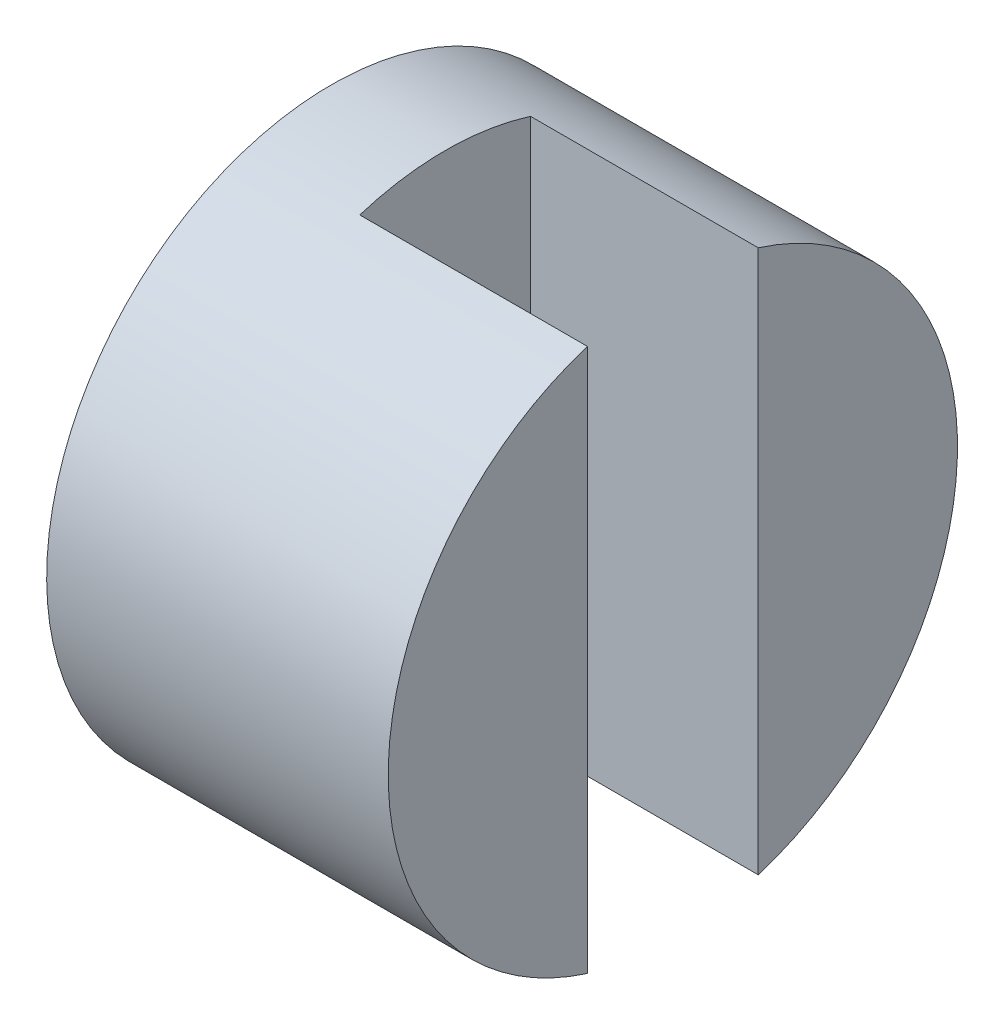
SolidWorks part; units mm, degrees
ref_plane "Front Plane" through (0, 0, 0) normal (0, 0, 1) x (1, 0, 0)
ref_plane "Top Plane" through (0, 0, 0) normal (0, 1, 0) x (1, 0, 0)
ref_plane "Right Plane" through (0, 0, 0) normal (1, 0, 0) x (0, 0, -1)
sketch "Sketch2" plane through (0, 0, 0) normal (1, 0, 0) x (0, 0, -1)
  circle A0 centre (0, 0) radius 5
extrude "Boss-Extrude1" add sketch "Sketch2" along normal blind 6
sketch "Sketch3" plane through (6, 0, 0) normal (1, 0, 0) x (0, 0, -1)
  line L0 (-1.5, 4.7697) -> (-1.5, -4.7697)
  line L1 (1.5, 4.7697) -> (1.5, -4.7697)
  circle A0 centre (0, 0) radius 5 construction
  arc A1 (-1.5, -4.7697) -> (1.5, -4.7697) centre (0, 0) ccw
  arc A2 (1.5, 4.7697) -> (-1.5, 4.7697) centre (0, 0) ccw
  dimension "D1" = 3
extrude "Cut-Extrude1" cut sketch "Sketch3" against normal blind 4
